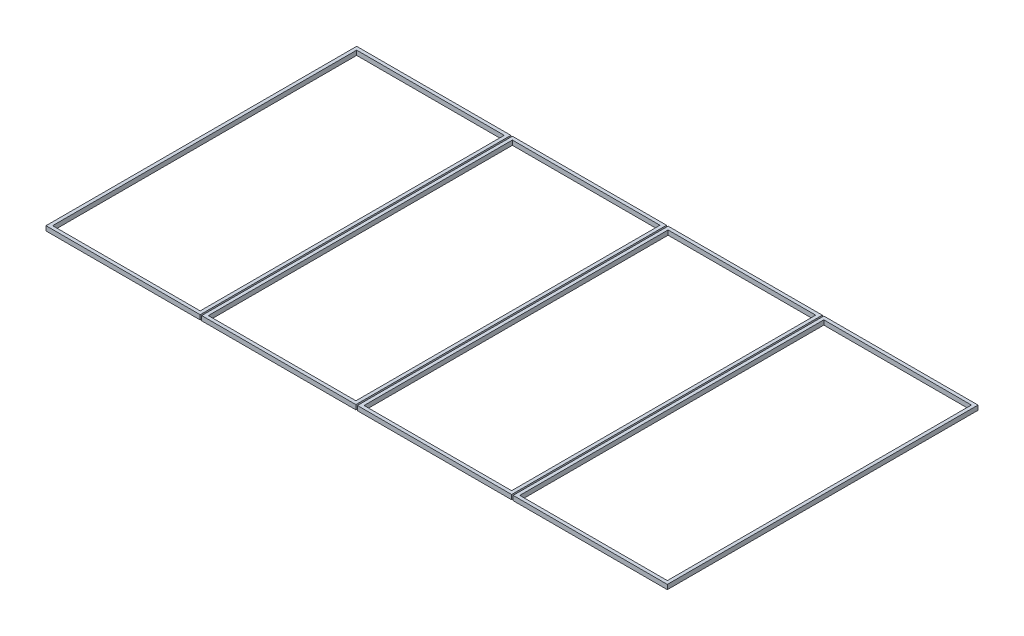
SolidWorks part; units mm, degrees
ref_plane "Front Plane" through (0, 0, 0) normal (0, 0, 1) x (1, 0, 0)
ref_plane "Top Plane" through (0, 0, 0) normal (0, 1, 0) x (1, 0, 0)
ref_plane "Right Plane" through (0, 0, 0) normal (1, 0, 0) x (0, 0, -1)
sketch "Sketch1" plane through (0, 0, 0) normal (0, 1, 0) x (1, 0, 0)
  line L2 (0, 0) -> (0, 1220)
  line L3 (0, 1220) -> (605.5, 1220)
  line L4 (2440, 0) -> (2440, 1220)
  line L5 (13, 1207) -> (592.5, 1207)
  line L10 (13, 1207) -> (13, 13)
  line L11 (13, 13) -> (592.5, 13)
  line L12 (592.5, 1207) -> (592.5, 13)
  line L13 (624.5, 1207) -> (1204, 1207)
  line L14 (624.5, 1207) -> (624.5, 13)
  line L15 (624.5, 13) -> (1204, 13)
  line L16 (1204, 1207) -> (1204, 13)
  line L17 (0, 0) -> (13, 0)
  line L18 (13, 0) -> (592.5, 0)
  line L19 (592.5, 0) -> (605.5, 0)
  line L20 (624.5, 0) -> (1204, 0)
  line L21 (1236, 13) -> (1815.5, 13)
  line L22 (1236, 13) -> (1236, 1207)
  line L23 (1236, 1207) -> (1815.5, 1207)
  line L24 (1815.5, 13) -> (1815.5, 1207)
  line L25 (605.5, 0) -> (611.5, 0) construction
  line L26 (1236, 0) -> (1815.5, 0)
  line L27 (611.5, 0) -> (624.5, 0)
  line L28 (1847.5, 0) -> (2427, 0)
  line L29 (2427, 0) -> (2440, 0)
  line L31 (1847.5, 1207) -> (2427, 1207)
  line L32 (1847.5, 1207) -> (1847.5, 13)
  line L33 (1847.5, 13) -> (2427, 13)
  line L34 (2427, 1207) -> (2427, 13)
  line L48 (1204, 0) -> (1217, 0)
  line L49 (1217, 0) -> (1223, 0) construction
  line L50 (1223, 0) -> (1236, 0)
  line L51 (1815.5, 0) -> (1828.5, 0)
  line L52 (1828.5, 0) -> (1834.5, 0) construction
  line L53 (1834.5, 0) -> (1847.5, 0)
  line L54 (605.5, 0) -> (605.5, 1220)
  line L55 (611.5, 0) -> (611.5, 1220)
  line L56 (1217, 0) -> (1217, 1220)
  line L57 (1223, 0) -> (1223, 1220)
  line L58 (1828.5, 0) -> (1828.5, 1220)
  line L59 (1834.5, 0) -> (1834.5, 1220)
  line L60 (611.5, 1220) -> (1217, 1220)
  line L61 (605.5, 1220) -> (611.5, 1220) construction
  line L62 (1223, 1220) -> (1828.5, 1220)
  line L63 (1217, 1220) -> (1223, 1220) construction
  line L64 (1834.5, 1220) -> (2440, 1220)
  line L65 (1828.5, 1220) -> (1834.5, 1220) construction
  line L66 (19.5, 1200.5) -> (586, 1200.5) construction
  line L67 (586, 1200.5) -> (586, 19.5) construction
  line L68 (19.5, 19.5) -> (586, 19.5) construction
  line L69 (19.5, 1200.5) -> (19.5, 19.5) construction
  dimension "sheet_length" = 2440
  dimension "sheet_width" = 1220
  dimension "D8" = 13
  dimension "D3" = 13
  dimension "D4" = 13
  dimension "D9" = 13
  dimension "D12" = 6
  dimension "D7" = 611.5
  dimension "quarter_panel_space" = 566.5
  dimension "D5" = 1181
  dimension "D6" = 6.5
extrude "Boss.-Extru.1" add sketch "Sketch1" along normal blind 18
equation "\"D12@Sketch1\"=\"tool_diameter\""
equation "\"tool_diameter\"=6"
equation "\"material_thickness\"=18"
equation "\"clearance_tight\"=0.1"
equation "\"D1@Boss.-Extru.1\"=\"material_thickness\""
equation "\"big_holes\"=56"
equation "\"tab_thickness\" = 25"
equation "\"tab_height\" = 3"
equation "\"D6@Sketch1\"=\"tool_diameter\" + \"clearance_loose\""
equation "\"D5@Extrude-Thin1\"=\"tab_thickness\""
equation "\"D1@Extrude-Thin1\"=\"tab_height\""
equation "\"clearance_loose\"=0.5"
equation "\"small_holes\"=10"
equation "\"string\"= 2 * \"tool_diameter\" / 2 * cos ( 45deg )"
equation "\"angle\"= IIF ( \"string\" < \"limit\" , 45 , ( 180 - 2 * arcsin ( \"ThicknessVStool_dia\" ) ) / 2 )"
equation "\"limit\"= \"material_thickness\" / 2 * 9 / 10"
equation "\"ThicknessVStool_dia\"= IIF ( \"limit\" / \"tool_diameter\" > 1 , 1 , \"limit\" / \"tool_diameter\" )"
